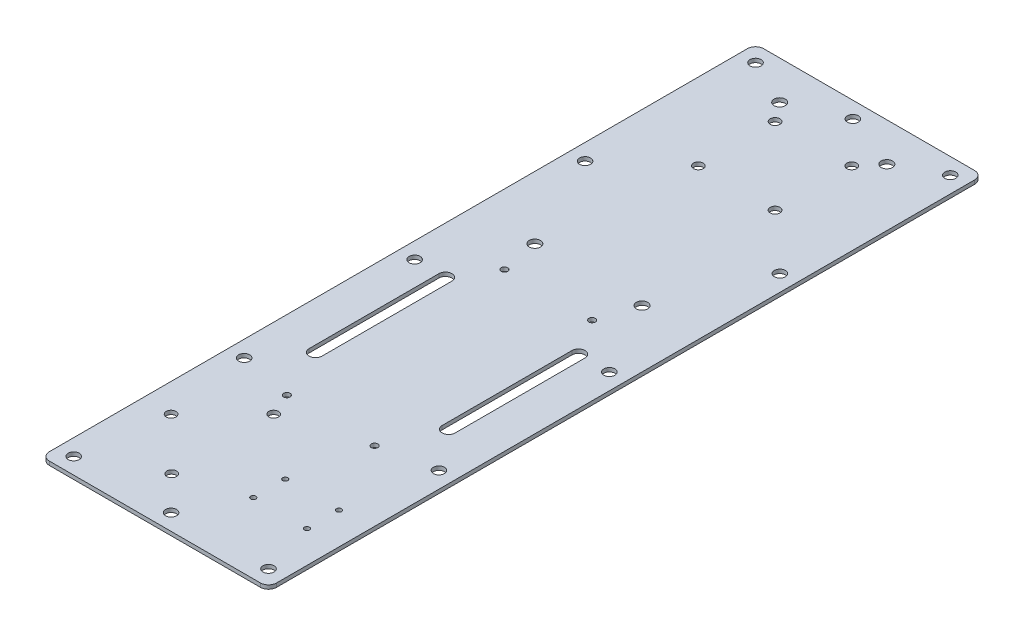
SolidWorks part; units mm, degrees
ref_plane "Front Plane" through (0, 0, 0) normal (0, 0, 1) x (1, 0, 0)
ref_plane "Top Plane" through (0, 0, 0) normal (0, 1, 0) x (1, 0, 0)
ref_plane "Right Plane" through (0, 0, 0) normal (1, 0, 0) x (0, 0, -1)
sketch "Sketch2" plane through (0, 0, 0) normal (0, 1, 0) x (1, 0, 0)
  line L0 (-44.45, 0) -> (44.45, 0) construction
  line L1 (-41.275, 139.7) -> (41.275, 139.7)
  line L2 (-44.45, 136.525) -> (-44.45, -136.525)
  line L3 (-41.275, -139.7) -> (41.275, -139.7)
  line L4 (44.45, 136.525) -> (44.45, -136.525)
  line L5 (0, 139.7) -> (0, -139.7) construction
  arc A0 (-44.45, -136.525) -> (-41.275, -139.7) centre (-41.275, -136.525) ccw
  arc A1 (41.275, -139.7) -> (44.45, -136.525) centre (41.275, -136.525) ccw
  arc A2 (41.275, 139.7) -> (44.45, 136.525) centre (41.275, 136.525) cw
  arc A3 (-41.275, 139.7) -> (-44.45, 136.525) centre (-41.275, 136.525) ccw
  point P8 (0, 0)
  point P13 (-44.45, -139.7)
  point P16 (44.45, -139.7)
  point P21 (-44.45, 139.7)
  dimension "D3" = 3.175
  dimension "D1" = 279.4
  dimension "D2" = 88.9
extrude "Plate Thickness" add sketch "Sketch2" along normal blind 1.5 contours L2 A0 L3 A1 L4 A2 L1 A3
sketch "Sketch3" plane through (0, 1.5, 0) normal (0, 1, 0) x (1, 0, 0)
  line L0 (-44.45, 136.525) -> (-44.45, -136.525) construction
  line L1 (-41.275, 139.7) -> (41.275, 139.7) construction
  line L4 (0, 139.7) -> (0, -139.7) construction
  line L5 (-41.275, -139.7) -> (41.275, -139.7) construction
  circle A0 centre (-38.1, 133.35) radius 2.159
  circle A1 centre (-38.1, 66.675) radius 2.159
  circle A2 centre (-38.1, -66.675) radius 2.159
  circle A3 centre (-38.1, -133.35) radius 2.159
  circle A4 centre (38.1, -133.35) radius 2.159
  circle A5 centre (38.1, -66.675) radius 2.159
  circle A6 centre (38.1, 66.675) radius 2.159
  circle A7 centre (38.1, 133.35) radius 2.159
  circle A8 centre (0, 133.35) radius 2.159
  circle A9 centre (0, -133.35) radius 2.159
  circle A10 centre (-38.1, 0) radius 2.159
  circle A11 centre (38.1, 0) radius 2.159
  dimension "D1" = 4.318
  dimension "D4" = 4.318
  dimension "D2" = 6.35
  dimension "D3" = 6.35
  dimension "D5" = 66.675
  dimension "D6" = 6.35
  dimension "D7" = 66.675
extrude "Mounting holes" cut sketch "Sketch3" against normal through all
sketch "Sketch4" plane through (0, 1.5, 0) normal (0, 1, 0) x (1, 0, 0)
  line L0 (-19.9374, 28.8942) -> (21.9726, 28.8942) construction
  line L1 (1.0176, 0) -> (1.0176, 139.7) construction
  circle A0 centre (-19.9374, 124.6522) radius 2.2225
  circle A1 centre (-19.9374, 28.8942) radius 2.2225
  circle A2 centre (21.9726, 28.8942) radius 2.2225
  circle A3 centre (21.9726, 124.6522) radius 2.2225
  point P13 (1.0176, 28.8942)
  dimension "D1" = 4.445
  dimension "D2" = 95.758
  dimension "D3" = 41.91
extrude "Jetson Holes (w/ mount)" cut sketch "Sketch4" against normal through all
sketch "Sketch5" plane through (0, 1.5, 0) normal (0, 1, 0) x (1, 0, 0)
  circle A1 centre (-14.3419, 117.2351) radius 1.905
  circle A3 centre (15.6555, 117.2351) radius 1.905
  circle A4 centre (15.6555, 87.2377) radius 1.905
  circle A5 centre (-14.3419, 87.2377) radius 1.905
  dimension "D1" = 3.81
  dimension "D2" = 29.9974
  dimension "D3" = 29.9974
extrude "PDB holes" cut sketch "Sketch5" against normal through all
sketch "Sketch6" plane through (0, 1.5, 0) normal (0, 1, 0) x (1, 0, 0)
  circle A6 centre (-13.0457, -120.0719) radius 1.905
  circle A7 centre (-13.2798, -79.9406) radius 1.905
  circle A8 centre (-33.3458, -100.0059) radius 1.905
  point P0 (0, 0)
  point P6 (0, 0)
  point P9 (-11.5149, -33.3527)
  point P12 (-11.5149, 4.8614)
  point P15 (0, 0)
  point P16 (-31.815, -14.8505)
  dimension "D5" = 40.132
  dimension "D6" = 20.066
  dimension "D7" = 20.066
  dimension "D8" = 3.81
extrude "Lidar Holes" cut sketch "Sketch6" against normal through all
sketch "Sketch7" plane through (0, 1.5, 0) normal (0, 1, 0) x (1, 0, 0)
  line L0 (0, 139.7) -> (0, -139.7) construction
  line L1 (-41.275, 139.7) -> (41.275, 139.7) construction
  line L2 (-41.275, -139.7) -> (41.275, -139.7) construction
  line L3 (17.145, 14.1724) -> (-17.145, 14.1724) construction
  circle A0 centre (-17.145, 14.1724) radius 1.27
  circle A1 centre (-17.145, -70.9176) radius 1.27
  circle A2 centre (17.145, -70.9176) radius 1.27
  circle A3 centre (17.145, 14.1724) radius 1.27
  point P14 (0, 14.1724)
  dimension "D1" = 2.54
  dimension "D2" = 85.09
  dimension "D3" = 34.29
extrude "PixHawk Holes" cut sketch "Sketch7" against normal through all
sketch "Sketch8" plane through (0, 1.5, 0) normal (0, 1, 0) x (1, 0, 0)
  line L0 (0, 139.7) -> (0, -115.5095) construction
  line L1 (-41.275, 139.7) -> (41.275, 139.7) construction
  line L2 (-26.035, -0.006) -> (-26.035, -50.806) construction
  line L3 (-23.495, -0.006) -> (-23.495, -50.806)
  line L4 (-28.575, -0.006) -> (-28.575, -50.806)
  line L5 (26.035, -0.006) -> (26.035, -50.806) construction
  line L6 (23.495, -0.006) -> (23.495, -50.806)
  line L7 (28.575, -0.006) -> (28.575, -50.806)
  arc A0 (-23.495, -0.006) -> (-28.575, -0.006) centre (-26.035, -0.006) ccw
  arc A1 (-28.575, -50.806) -> (-23.495, -50.806) centre (-26.035, -50.806) ccw
  arc A2 (23.495, -0.006) -> (28.575, -0.006) centre (26.035, -0.006) cw
  arc A3 (28.575, -50.806) -> (23.495, -50.806) centre (26.035, -50.806) cw
  point P7 (-26.035, -25.406)
  point P14 (26.035, -25.406)
  dimension "D1" = 50.8
  dimension "D2" = 5.08
  dimension "D3" = 26.035
extrude "Battery Holes" cut sketch "Sketch8" against normal through all
sketch "Sketch 9" plane through (0, 0, 0) normal (0, -1, 0) x (1, 0, 0)
  circle A0 centre (31.997, 112.1883) radius 1
  circle A1 centre (10.997, 112.1883) radius 1
  circle A2 centre (10.997, 99.6883) radius 1
  circle A3 centre (31.997, 99.6883) radius 1
  point P4 (26.3653, 110.1835)
  point P7 (0, 0)
  point P8 (0, 0)
  point P9 (10.997, 99.6883)
  point P12 (0, 0)
  point P13 (26.3653, 99.6883)
  point P14 (0, 0)
  point P15 (10.997, 110.1835)
  dimension "D1" = 21
  dimension "D2" = 12.5
  dimension "D3" = 21
  dimension "D4" = 12.5
extrude "Ventral Boardcam Holles" cut sketch "Sketch 9" against normal through all
